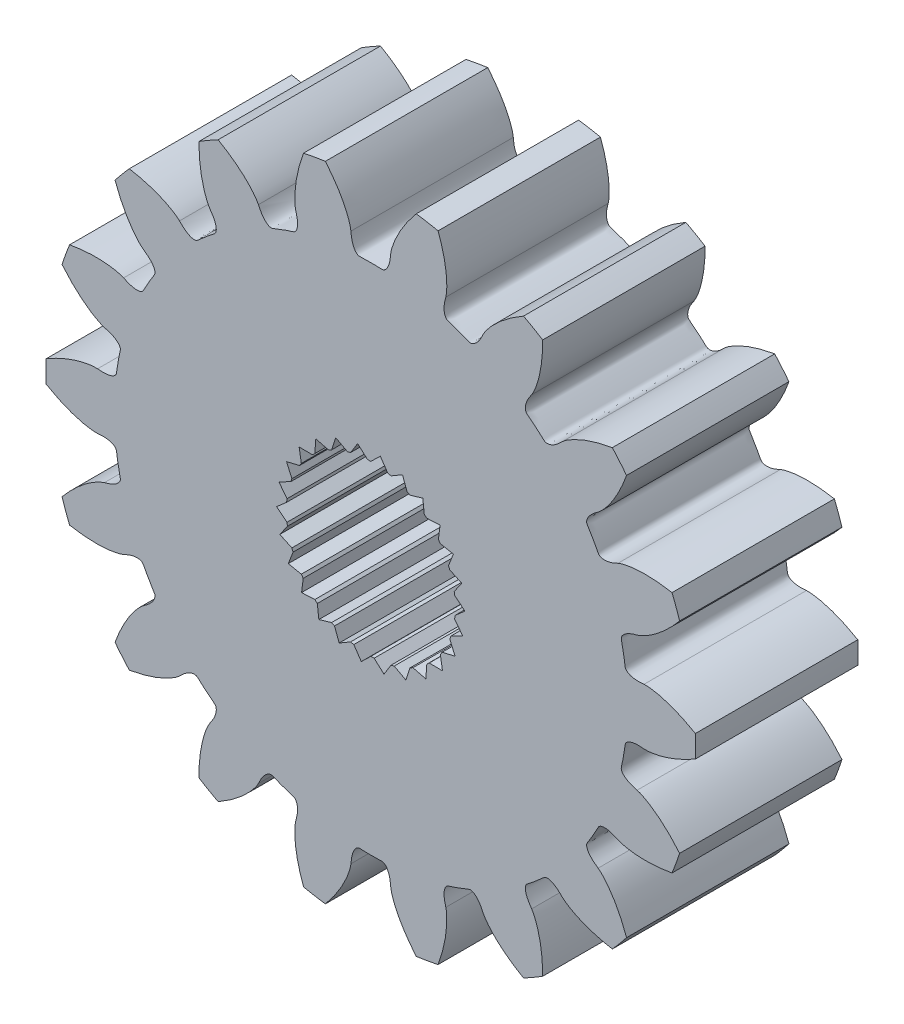
SolidWorks part; units mm, degrees
ref_plane "Ön Düzlem" through (0, 0, 0) normal (0, 0, 1) x (1, 0, 0)
ref_plane "Üst Düzlem" through (0, 0, 0) normal (0, 1, 0) x (1, 0, 0)
ref_plane "Sağ Düzlem" through (0, 0, 0) normal (1, 0, 0) x (0, 0, -1)
sketch "Model" plane through (0, 0, 0) normal (0, 0, 1) x (1, 0, 0)
  arc A0 (-4.7019, 8.8256) -> (-5.2923, 8.4848) centre (0, 0) ccw
  arc A1 (-7.4369, 6.6852) -> (-7.8751, 6.1631) centre (0, 0) ccw
  arc A2 (-9.2749, 3.7385) -> (-9.508, 3.098) centre (0, 0) ccw
  arc A3 (-9.9942, 0.3408) -> (-9.9942, -0.3408) centre (0, 0) ccw
  arc A4 (-9.508, -3.098) -> (-9.2749, -3.7385) centre (0, 0) ccw
  arc A5 (-7.8751, -6.1631) -> (-7.4369, -6.6852) centre (0, 0) ccw
  arc A6 (-5.2923, -8.4848) -> (-4.7019, -8.8256) centre (0, 0) ccw
  arc A7 (-2.0711, -9.7832) -> (-1.3998, -9.9015) centre (0, 0) ccw
  arc A8 (1.3998, -9.9015) -> (2.0711, -9.7832) centre (0, 0) ccw
  arc A9 (4.7019, -8.8256) -> (5.2923, -8.4848) centre (0, 0) ccw
  arc A10 (7.4369, -6.6852) -> (7.8751, -6.1631) centre (0, 0) ccw
  arc A11 (9.2749, -3.7385) -> (9.508, -3.098) centre (0, 0) ccw
  arc A12 (9.9942, -0.3408) -> (9.9942, 0.3408) centre (0, 0) ccw
  arc A13 (9.508, 3.098) -> (9.2749, 3.7385) centre (0, 0) ccw
  arc A14 (7.8751, 6.1631) -> (7.4369, 6.6852) centre (0, 0) ccw
  arc A15 (5.2923, 8.4848) -> (4.7019, 8.8256) centre (0, 0) ccw
  arc A16 (2.0711, 9.7832) -> (1.3998, 9.9015) centre (0, 0) ccw
  arc A17 (-1.3998, 9.9015) -> (-2.0711, 9.7832) centre (0, 0) ccw
  spline S0 degree 3 poles (-3.4596, 7.7174) (-3.4766, 7.7481) (-3.5107, 7.8095) (-3.5724, 7.8948) (-3.6377, 7.9773) (-3.73, 8.083) (-3.8528, 8.2083) (-4.0096, 8.3488) (-4.1738, 8.4805) (-4.3445, 8.6036) (-4.5202, 8.7195) (-4.6414, 8.7902) (-4.7019, 8.8256) knots -0.168309 -0.168309 -0.168309 -0.168309 -0.157796 -0.147277 -0.136757 -0.126236 -0.105199 -0.08416 -0.06312 -0.04208 -0.02104 0 0 0 0
  spline S1 degree 3 poles (-5.2923, 8.4848) (-5.2919, 8.4147) (-5.2912, 8.2744) (-5.2787, 8.0643) (-5.2574, 7.8549) (-5.2255, 7.6468) (-5.1822, 7.4408) (-5.1351, 7.2718) (-5.0897, 7.139) (-5.0509, 7.0412) (-5.0079, 6.9451) (-4.9717, 6.8849) (-4.9537, 6.8548) knots -0.168309 -0.168309 -0.168309 -0.168309 -0.147269 -0.126229 -0.105189 -0.084149 -0.06311 -0.042073 -0.031553 -0.021033 -0.010514 0 0 0 0
  spline S2 degree 3 poles (-4.9537, 6.8548) (-4.9296, 6.8211) (-4.8815, 6.7537) (-4.8313, 6.6629) (-4.7979, 6.5872) (-4.7774, 6.5285) (-4.7628, 6.468) (-4.7564, 6.4061) (-4.761, 6.354) (-4.7741, 6.3146) (-4.7945, 6.2781) (-4.8353, 6.2449) (-4.9017, 6.196) (-4.9834, 6.1322) (-5.0778, 6.0514) (-5.1737, 5.9726) (-5.2507, 5.9031) (-5.3103, 5.8463) (-5.3502, 5.8119) (-5.3897, 5.798) (-5.4307, 5.792) (-5.4828, 5.7965) (-5.5427, 5.8136) (-5.5997, 5.8385) (-5.6539, 5.8688) (-5.7228, 5.9149) (-5.8035, 5.9801) (-5.8615, 6.0392) (-5.8905, 6.0688) knots -0.198614 -0.198614 -0.198614 -0.198614 -0.186198 -0.173785 -0.167576 -0.161368 -0.155161 -0.148957 -0.14276 -0.139657 -0.136554 -0.130358 -0.124146 -0.111726 -0.099307 -0.086888 -0.074468 -0.068256 -0.06206 -0.058957 -0.055854 -0.049658 -0.043453 -0.037246 -0.031038 -0.024829 -0.012416 0 0 0 0
  spline S3 degree 3 poles (-5.8905, 6.0688) (-5.917, 6.0918) (-5.9699, 6.1378) (-6.0572, 6.1969) (-6.1467, 6.2521) (-6.2696, 6.3198) (-6.4279, 6.3955) (-6.6232, 6.474) (-6.8226, 6.5415) (-7.0251, 6.5989) (-7.2299, 6.6476) (-7.3679, 6.6727) (-7.4369, 6.6852) knots -0.168309 -0.168309 -0.168309 -0.168309 -0.157796 -0.147277 -0.136757 -0.126236 -0.105199 -0.08416 -0.06312 -0.04208 -0.02104 0 0 0 0
  spline S4 degree 3 poles (-7.8751, 6.1631) (-7.8507, 6.0973) (-7.8021, 5.9657) (-7.7185, 5.7725) (-7.6269, 5.583) (-7.5257, 5.3984) (-7.4146, 5.2197) (-7.3125, 5.0769) (-7.2244, 4.9677) (-7.1545, 4.8891) (-7.0812, 4.8134) (-7.0267, 4.7693) (-6.9994, 4.7472) knots -0.168309 -0.168309 -0.168309 -0.168309 -0.147269 -0.126229 -0.105189 -0.084149 -0.06311 -0.042073 -0.031553 -0.021033 -0.010514 0 0 0 0
  spline S5 degree 3 poles (-6.9994, 4.7472) (-6.9653, 4.7237) (-6.897, 4.6769) (-6.8188, 4.6087) (-6.7615, 4.5489) (-6.7222, 4.5008) (-6.6878, 4.4489) (-6.6605, 4.393) (-6.6471, 4.3424) (-6.6459, 4.301) (-6.6526, 4.2597) (-6.6796, 4.2145) (-6.7252, 4.1459) (-6.7802, 4.0579) (-6.8413, 3.9498) (-6.9044, 3.8429) (-6.953, 3.7513) (-6.9896, 3.6775) (-7.0153, 3.6315) (-7.0477, 3.605) (-7.0842, 3.5853) (-7.1347, 3.5717) (-7.1968, 3.5673) (-7.2589, 3.5712) (-7.3202, 3.5811) (-7.4007, 3.6009) (-7.4988, 3.6346) (-7.5735, 3.6703) (-7.6109, 3.6881) knots -0.198614 -0.198614 -0.198614 -0.198614 -0.186198 -0.173785 -0.167576 -0.161368 -0.155161 -0.148957 -0.14276 -0.139657 -0.136554 -0.130358 -0.124146 -0.111726 -0.099307 -0.086888 -0.074468 -0.068256 -0.06206 -0.058957 -0.055854 -0.049658 -0.043453 -0.037246 -0.031038 -0.024829 -0.012416 0 0 0 0
  spline S6 degree 3 poles (-7.6109, 3.6881) (-7.6436, 3.7007) (-7.7092, 3.7258) (-7.8113, 3.7515) (-7.9144, 3.7727) (-8.053, 3.7944) (-8.2276, 3.8114) (-8.438, 3.8183) (-8.6485, 3.8135) (-8.8584, 3.7982) (-9.0675, 3.774) (-9.2058, 3.7503) (-9.2749, 3.7385) knots -0.168309 -0.168309 -0.168309 -0.168309 -0.157796 -0.147277 -0.136757 -0.126236 -0.105199 -0.08416 -0.06312 -0.04208 -0.02104 0 0 0 0
  spline S7 degree 3 poles (-9.508, 3.098) (-9.4627, 3.0444) (-9.3719, 2.9374) (-9.2273, 2.7845) (-9.0764, 2.6378) (-8.9182, 2.4989) (-8.7526, 2.369) (-8.6079, 2.2697) (-8.4878, 2.1972) (-8.3952, 2.1472) (-8.3004, 2.1012) (-8.2341, 2.0784) (-8.2009, 2.0669) knots -0.168309 -0.168309 -0.168309 -0.168309 -0.147269 -0.126229 -0.105189 -0.084149 -0.06311 -0.042073 -0.031553 -0.021033 -0.010514 0 0 0 0
  spline S8 degree 3 poles (-8.2009, 2.0669) (-8.1609, 2.0566) (-8.0807, 2.0359) (-7.9838, 1.9986) (-7.9095, 1.962) (-7.8561, 1.9302) (-7.8061, 1.8933) (-7.7614, 1.85) (-7.7314, 1.8071) (-7.7161, 1.7686) (-7.7083, 1.7275) (-7.7182, 1.6758) (-7.7376, 1.5957) (-7.7592, 1.4942) (-7.7796, 1.3718) (-7.8023, 1.2497) (-7.8167, 1.147) (-7.8259, 1.0651) (-7.8343, 1.0131) (-7.8556, 0.9771) (-7.8832, 0.9462) (-7.926, 0.9161) (-7.9829, 0.8907) (-8.0425, 0.8731) (-8.1036, 0.8615) (-8.1859, 0.8525) (-8.2897, 0.8507) (-8.3721, 0.8586) (-8.4133, 0.8626) knots -0.198614 -0.198614 -0.198614 -0.198614 -0.186198 -0.173785 -0.167576 -0.161368 -0.155161 -0.148957 -0.14276 -0.139657 -0.136554 -0.130358 -0.124146 -0.111726 -0.099307 -0.086888 -0.074468 -0.068256 -0.06206 -0.058957 -0.055854 -0.049658 -0.043453 -0.037246 -0.031038 -0.024829 -0.012416 0 0 0 0
  spline S9 degree 3 poles (-8.4133, 0.8626) (-8.4484, 0.8632) (-8.5185, 0.8644) (-8.6233, 0.8536) (-8.7274, 0.8383) (-8.8651, 0.8112) (-9.035, 0.7675) (-9.2351, 0.702) (-9.4312, 0.6256) (-9.6232, 0.5394) (-9.8114, 0.4451) (-9.9333, 0.3756) (-9.9942, 0.3408) knots -0.168309 -0.168309 -0.168309 -0.168309 -0.157796 -0.147277 -0.136757 -0.126236 -0.105199 -0.08416 -0.06312 -0.04208 -0.02104 0 0 0 0
  spline S10 degree 3 poles (-9.9942, -0.3408) (-9.9333, -0.3756) (-9.8114, -0.4451) (-9.6232, -0.5394) (-9.4312, -0.6256) (-9.2351, -0.702) (-9.035, -0.7675) (-8.8651, -0.8112) (-8.7274, -0.8383) (-8.6233, -0.8536) (-8.5185, -0.8644) (-8.4484, -0.8632) (-8.4133, -0.8626) knots -0.168309 -0.168309 -0.168309 -0.168309 -0.147269 -0.126229 -0.105189 -0.084149 -0.06311 -0.042073 -0.031553 -0.021033 -0.010514 0 0 0 0
  spline S11 degree 3 poles (-8.4133, -0.8626) (-8.3721, -0.8586) (-8.2897, -0.8507) (-8.1859, -0.8525) (-8.1036, -0.8615) (-8.0425, -0.8731) (-7.9829, -0.8907) (-7.926, -0.9161) (-7.8832, -0.9462) (-7.8556, -0.9771) (-7.8343, -1.0131) (-7.8259, -1.0651) (-7.8167, -1.147) (-7.8023, -1.2497) (-7.7796, -1.3718) (-7.7592, -1.4942) (-7.7376, -1.5957) (-7.7182, -1.6758) (-7.7083, -1.7275) (-7.7161, -1.7686) (-7.7314, -1.8071) (-7.7614, -1.85) (-7.8061, -1.8933) (-7.8561, -1.9302) (-7.9095, -1.962) (-7.9838, -1.9986) (-8.0807, -2.0359) (-8.1609, -2.0566) (-8.2009, -2.0669) knots -0.198614 -0.198614 -0.198614 -0.198614 -0.186198 -0.173785 -0.167576 -0.161368 -0.155161 -0.148957 -0.14276 -0.139657 -0.136554 -0.130358 -0.124146 -0.111726 -0.099307 -0.086888 -0.074468 -0.068256 -0.06206 -0.058957 -0.055854 -0.049658 -0.043453 -0.037246 -0.031038 -0.024829 -0.012416 0 0 0 0
  spline S12 degree 3 poles (-8.2009, -2.0669) (-8.2341, -2.0784) (-8.3004, -2.1012) (-8.3952, -2.1472) (-8.4878, -2.1972) (-8.6079, -2.2697) (-8.7526, -2.369) (-8.9182, -2.4989) (-9.0764, -2.6378) (-9.2273, -2.7845) (-9.3719, -2.9374) (-9.4627, -3.0444) (-9.508, -3.098) knots -0.168309 -0.168309 -0.168309 -0.168309 -0.157796 -0.147277 -0.136757 -0.126236 -0.105199 -0.08416 -0.06312 -0.04208 -0.02104 0 0 0 0
  spline S13 degree 3 poles (-9.2749, -3.7385) (-9.2058, -3.7503) (-9.0675, -3.774) (-8.8584, -3.7982) (-8.6485, -3.8135) (-8.438, -3.8183) (-8.2276, -3.8114) (-8.053, -3.7944) (-7.9144, -3.7727) (-7.8113, -3.7515) (-7.7092, -3.7258) (-7.6436, -3.7007) (-7.6109, -3.6881) knots -0.168309 -0.168309 -0.168309 -0.168309 -0.147269 -0.126229 -0.105189 -0.084149 -0.06311 -0.042073 -0.031553 -0.021033 -0.010514 0 0 0 0
  spline S14 degree 3 poles (-7.6109, -3.6881) (-7.5735, -3.6703) (-7.4988, -3.6346) (-7.4007, -3.6009) (-7.3202, -3.5811) (-7.2589, -3.5712) (-7.1968, -3.5673) (-7.1347, -3.5717) (-7.0842, -3.5853) (-7.0477, -3.605) (-7.0153, -3.6315) (-6.9896, -3.6775) (-6.953, -3.7513) (-6.9044, -3.8429) (-6.8413, -3.9498) (-6.7802, -4.0579) (-6.7252, -4.1459) (-6.6796, -4.2145) (-6.6526, -4.2597) (-6.6459, -4.301) (-6.6471, -4.3424) (-6.6605, -4.393) (-6.6878, -4.4489) (-6.7222, -4.5008) (-6.7615, -4.5489) (-6.8188, -4.6087) (-6.897, -4.6769) (-6.9653, -4.7237) (-6.9994, -4.7472) knots -0.198614 -0.198614 -0.198614 -0.198614 -0.186198 -0.173785 -0.167576 -0.161368 -0.155161 -0.148957 -0.14276 -0.139657 -0.136554 -0.130358 -0.124146 -0.111726 -0.099307 -0.086888 -0.074468 -0.068256 -0.06206 -0.058957 -0.055854 -0.049658 -0.043453 -0.037246 -0.031038 -0.024829 -0.012416 0 0 0 0
  spline S15 degree 3 poles (-6.9994, -4.7472) (-7.0267, -4.7693) (-7.0812, -4.8134) (-7.1545, -4.8891) (-7.2244, -4.9677) (-7.3125, -5.0769) (-7.4146, -5.2197) (-7.5257, -5.3984) (-7.6269, -5.583) (-7.7185, -5.7725) (-7.8021, -5.9657) (-7.8507, -6.0973) (-7.8751, -6.1631) knots -0.168309 -0.168309 -0.168309 -0.168309 -0.157796 -0.147277 -0.136757 -0.126236 -0.105199 -0.08416 -0.06312 -0.04208 -0.02104 0 0 0 0
  spline S16 degree 3 poles (-7.4369, -6.6852) (-7.3679, -6.6727) (-7.2299, -6.6476) (-7.0251, -6.5989) (-6.8226, -6.5415) (-6.6232, -6.474) (-6.4279, -6.3955) (-6.2696, -6.3198) (-6.1467, -6.2521) (-6.0572, -6.1969) (-5.9699, -6.1378) (-5.917, -6.0918) (-5.8905, -6.0688) knots -0.168309 -0.168309 -0.168309 -0.168309 -0.147269 -0.126229 -0.105189 -0.084149 -0.06311 -0.042073 -0.031553 -0.021033 -0.010514 0 0 0 0
  spline S17 degree 3 poles (-5.8905, -6.0688) (-5.8615, -6.0392) (-5.8035, -5.9801) (-5.7228, -5.9149) (-5.6539, -5.8688) (-5.5997, -5.8385) (-5.5427, -5.8136) (-5.4828, -5.7965) (-5.4307, -5.792) (-5.3897, -5.798) (-5.3502, -5.8119) (-5.3103, -5.8463) (-5.2507, -5.9031) (-5.1737, -5.9726) (-5.0778, -6.0514) (-4.9834, -6.1322) (-4.9017, -6.196) (-4.8353, -6.2449) (-4.7945, -6.2781) (-4.7741, -6.3146) (-4.761, -6.354) (-4.7564, -6.4061) (-4.7628, -6.468) (-4.7774, -6.5285) (-4.7979, -6.5872) (-4.8313, -6.6629) (-4.8815, -6.7537) (-4.9296, -6.8211) (-4.9537, -6.8548) knots -0.198614 -0.198614 -0.198614 -0.198614 -0.186198 -0.173785 -0.167576 -0.161368 -0.155161 -0.148957 -0.14276 -0.139657 -0.136554 -0.130358 -0.124146 -0.111726 -0.099307 -0.086888 -0.074468 -0.068256 -0.06206 -0.058957 -0.055854 -0.049658 -0.043453 -0.037246 -0.031038 -0.024829 -0.012416 0 0 0 0
  spline S18 degree 3 poles (-4.9537, -6.8548) (-4.9717, -6.8849) (-5.0079, -6.9451) (-5.0509, -7.0412) (-5.0897, -7.139) (-5.1351, -7.2718) (-5.1822, -7.4408) (-5.2255, -7.6468) (-5.2574, -7.8549) (-5.2787, -8.0643) (-5.2912, -8.2744) (-5.2919, -8.4147) (-5.2923, -8.4848) knots -0.168309 -0.168309 -0.168309 -0.168309 -0.157796 -0.147277 -0.136757 -0.126236 -0.105199 -0.08416 -0.06312 -0.04208 -0.02104 0 0 0 0
  spline S19 degree 3 poles (-4.7019, -8.8256) (-4.6414, -8.7902) (-4.5202, -8.7195) (-4.3445, -8.6036) (-4.1738, -8.4805) (-4.0096, -8.3488) (-3.8528, -8.2083) (-3.73, -8.083) (-3.6377, -7.9773) (-3.5724, -7.8948) (-3.5107, -7.8095) (-3.4766, -7.7481) (-3.4596, -7.7174) knots -0.168309 -0.168309 -0.168309 -0.168309 -0.147269 -0.126229 -0.105189 -0.084149 -0.06311 -0.042073 -0.031553 -0.021033 -0.010514 0 0 0 0
  spline S20 degree 3 poles (-3.4596, -7.7174) (-3.4425, -7.6797) (-3.4081, -7.6044) (-3.3546, -7.5155) (-3.3057, -7.4487) (-3.2651, -7.4016) (-3.22, -7.3587) (-3.1697, -7.3222) (-3.1222, -7.3002) (-3.0816, -7.2918) (-3.0398, -7.2913) (-2.9905, -7.3099) (-2.9151, -7.343) (-2.8189, -7.3819) (-2.7018, -7.4232) (-2.5856, -7.4668) (-2.4869, -7.4988) (-2.4078, -7.522) (-2.3581, -7.5394) (-2.3264, -7.5666) (-2.3007, -7.5992) (-2.2785, -7.6465) (-2.2634, -7.7069) (-2.2564, -7.7687) (-2.2556, -7.8309) (-2.2611, -7.9135) (-2.2772, -8.016) (-2.2994, -8.0958) (-2.3104, -8.1357) knots -0.198614 -0.198614 -0.198614 -0.198614 -0.186198 -0.173785 -0.167576 -0.161368 -0.155161 -0.148957 -0.14276 -0.139657 -0.136554 -0.130358 -0.124146 -0.111726 -0.099307 -0.086888 -0.074468 -0.068256 -0.06206 -0.058957 -0.055854 -0.049658 -0.043453 -0.037246 -0.031038 -0.024829 -0.012416 0 0 0 0
  spline S21 degree 3 poles (-2.3104, -8.1357) (-2.3171, -8.1701) (-2.3305, -8.239) (-2.3381, -8.3441) (-2.3411, -8.4492) (-2.3383, -8.5895) (-2.3247, -8.7645) (-2.295, -8.9729) (-2.2538, -9.1793) (-2.2022, -9.3833) (-2.1421, -9.5851) (-2.0948, -9.7171) (-2.0711, -9.7832) knots -0.168309 -0.168309 -0.168309 -0.168309 -0.157796 -0.147277 -0.136757 -0.126236 -0.105199 -0.08416 -0.06312 -0.04208 -0.02104 0 0 0 0
  spline S22 degree 3 poles (-1.3998, -9.9015) (-1.355, -9.8476) (-1.2654, -9.7396) (-1.1399, -9.5707) (-1.0216, -9.3966) (-0.9123, -9.2167) (-0.8131, -9.031) (-0.7405, -8.8713) (-0.6899, -8.7404) (-0.6568, -8.6405) (-0.6279, -8.5392) (-0.617, -8.4699) (-0.6115, -8.4353) knots -0.168309 -0.168309 -0.168309 -0.168309 -0.147269 -0.126229 -0.105189 -0.084149 -0.06311 -0.042073 -0.031553 -0.021033 -0.010514 0 0 0 0
  spline S23 degree 3 poles (-0.6115, -8.4353) (-0.6082, -8.394) (-0.6018, -8.3114) (-0.5819, -8.2096) (-0.5588, -8.1301) (-0.5367, -8.072) (-0.509, -8.0163) (-0.4742, -7.9647) (-0.4371, -7.9278) (-0.4018, -7.906) (-0.3627, -7.8912) (-0.31, -7.8919) (-0.2278, -7.8972) (-0.1242, -7.9008) (0, -7.8996) (0.1242, -7.9008) (0.2278, -7.8972) (0.31, -7.8919) (0.3627, -7.8912) (0.4018, -7.906) (0.4371, -7.9278) (0.4742, -7.9647) (0.509, -8.0163) (0.5367, -8.072) (0.5588, -8.1301) (0.5819, -8.2096) (0.6018, -8.3114) (0.6082, -8.394) (0.6115, -8.4353) knots -0.198614 -0.198614 -0.198614 -0.198614 -0.186198 -0.173785 -0.167576 -0.161368 -0.155161 -0.148957 -0.14276 -0.139657 -0.136554 -0.130358 -0.124146 -0.111726 -0.099307 -0.086888 -0.074468 -0.068256 -0.06206 -0.058957 -0.055854 -0.049658 -0.043453 -0.037246 -0.031038 -0.024829 -0.012416 0 0 0 0
  spline S24 degree 3 poles (0.6115, -8.4353) (0.617, -8.4699) (0.6279, -8.5392) (0.6568, -8.6405) (0.6899, -8.7404) (0.7405, -8.8713) (0.8131, -9.031) (0.9123, -9.2167) (1.0216, -9.3966) (1.1399, -9.5707) (1.2654, -9.7396) (1.355, -9.8476) (1.3998, -9.9015) knots -0.168309 -0.168309 -0.168309 -0.168309 -0.157796 -0.147277 -0.136757 -0.126236 -0.105199 -0.08416 -0.06312 -0.04208 -0.02104 0 0 0 0
  spline S25 degree 3 poles (2.0711, -9.7832) (2.0948, -9.7171) (2.1421, -9.5851) (2.2022, -9.3833) (2.2538, -9.1793) (2.295, -8.9729) (2.3247, -8.7645) (2.3383, -8.5895) (2.3411, -8.4492) (2.3381, -8.3441) (2.3305, -8.239) (2.3171, -8.1701) (2.3104, -8.1357) knots -0.168309 -0.168309 -0.168309 -0.168309 -0.147269 -0.126229 -0.105189 -0.084149 -0.06311 -0.042073 -0.031553 -0.021033 -0.010514 0 0 0 0
  spline S26 degree 3 poles (2.3104, -8.1357) (2.2994, -8.0958) (2.2772, -8.016) (2.2611, -7.9135) (2.2556, -7.8309) (2.2564, -7.7687) (2.2634, -7.7069) (2.2785, -7.6465) (2.3007, -7.5992) (2.3264, -7.5666) (2.3581, -7.5394) (2.4078, -7.522) (2.4869, -7.4988) (2.5856, -7.4668) (2.7018, -7.4232) (2.8189, -7.3819) (2.9151, -7.343) (2.9905, -7.3099) (3.0398, -7.2913) (3.0816, -7.2918) (3.1222, -7.3002) (3.1697, -7.3222) (3.22, -7.3587) (3.2651, -7.4016) (3.3057, -7.4487) (3.3546, -7.5155) (3.4081, -7.6044) (3.4425, -7.6797) (3.4596, -7.7174) knots -0.198614 -0.198614 -0.198614 -0.198614 -0.186198 -0.173785 -0.167576 -0.161368 -0.155161 -0.148957 -0.14276 -0.139657 -0.136554 -0.130358 -0.124146 -0.111726 -0.099307 -0.086888 -0.074468 -0.068256 -0.06206 -0.058957 -0.055854 -0.049658 -0.043453 -0.037246 -0.031038 -0.024829 -0.012416 0 0 0 0
  spline S27 degree 3 poles (3.4596, -7.7174) (3.4766, -7.7481) (3.5107, -7.8095) (3.5724, -7.8948) (3.6377, -7.9773) (3.73, -8.083) (3.8528, -8.2083) (4.0096, -8.3488) (4.1738, -8.4805) (4.3445, -8.6036) (4.5202, -8.7195) (4.6414, -8.7902) (4.7019, -8.8256) knots -0.168309 -0.168309 -0.168309 -0.168309 -0.157796 -0.147277 -0.136757 -0.126236 -0.105199 -0.08416 -0.06312 -0.04208 -0.02104 0 0 0 0
  spline S28 degree 3 poles (5.2923, -8.4848) (5.2919, -8.4147) (5.2912, -8.2744) (5.2787, -8.0643) (5.2574, -7.8549) (5.2255, -7.6468) (5.1822, -7.4408) (5.1351, -7.2718) (5.0897, -7.139) (5.0509, -7.0412) (5.0079, -6.9451) (4.9717, -6.8849) (4.9537, -6.8548) knots -0.168309 -0.168309 -0.168309 -0.168309 -0.147269 -0.126229 -0.105189 -0.084149 -0.06311 -0.042073 -0.031553 -0.021033 -0.010514 0 0 0 0
  spline S29 degree 3 poles (4.9537, -6.8548) (4.9296, -6.8211) (4.8815, -6.7537) (4.8313, -6.6629) (4.7979, -6.5872) (4.7774, -6.5285) (4.7628, -6.468) (4.7564, -6.4061) (4.761, -6.354) (4.7741, -6.3146) (4.7945, -6.2781) (4.8353, -6.2449) (4.9017, -6.196) (4.9834, -6.1322) (5.0778, -6.0514) (5.1737, -5.9726) (5.2507, -5.9031) (5.3103, -5.8463) (5.3502, -5.8119) (5.3897, -5.798) (5.4307, -5.792) (5.4828, -5.7965) (5.5427, -5.8136) (5.5997, -5.8385) (5.6539, -5.8688) (5.7228, -5.9149) (5.8035, -5.9801) (5.8615, -6.0392) (5.8905, -6.0688) knots -0.198614 -0.198614 -0.198614 -0.198614 -0.186198 -0.173785 -0.167576 -0.161368 -0.155161 -0.148957 -0.14276 -0.139657 -0.136554 -0.130358 -0.124146 -0.111726 -0.099307 -0.086888 -0.074468 -0.068256 -0.06206 -0.058957 -0.055854 -0.049658 -0.043453 -0.037246 -0.031038 -0.024829 -0.012416 0 0 0 0
  spline S30 degree 3 poles (5.8905, -6.0688) (5.917, -6.0918) (5.9699, -6.1378) (6.0572, -6.1969) (6.1467, -6.2521) (6.2696, -6.3198) (6.4279, -6.3955) (6.6232, -6.474) (6.8226, -6.5415) (7.0251, -6.5989) (7.2299, -6.6476) (7.3679, -6.6727) (7.4369, -6.6852) knots -0.168309 -0.168309 -0.168309 -0.168309 -0.157796 -0.147277 -0.136757 -0.126236 -0.105199 -0.08416 -0.06312 -0.04208 -0.02104 0 0 0 0
  spline S31 degree 3 poles (7.8751, -6.1631) (7.8507, -6.0973) (7.8021, -5.9657) (7.7185, -5.7725) (7.6269, -5.583) (7.5257, -5.3984) (7.4146, -5.2197) (7.3125, -5.0769) (7.2244, -4.9677) (7.1545, -4.8891) (7.0812, -4.8134) (7.0267, -4.7693) (6.9994, -4.7472) knots -0.168309 -0.168309 -0.168309 -0.168309 -0.147269 -0.126229 -0.105189 -0.084149 -0.06311 -0.042073 -0.031553 -0.021033 -0.010514 0 0 0 0
  spline S32 degree 3 poles (6.9994, -4.7472) (6.9653, -4.7237) (6.897, -4.6769) (6.8188, -4.6087) (6.7615, -4.5489) (6.7222, -4.5008) (6.6878, -4.4489) (6.6605, -4.393) (6.6471, -4.3424) (6.6459, -4.301) (6.6526, -4.2597) (6.6796, -4.2145) (6.7252, -4.1459) (6.7802, -4.0579) (6.8413, -3.9498) (6.9044, -3.8429) (6.953, -3.7513) (6.9896, -3.6775) (7.0153, -3.6315) (7.0477, -3.605) (7.0842, -3.5853) (7.1347, -3.5717) (7.1968, -3.5673) (7.2589, -3.5712) (7.3202, -3.5811) (7.4007, -3.6009) (7.4988, -3.6346) (7.5735, -3.6703) (7.6109, -3.6881) knots -0.198614 -0.198614 -0.198614 -0.198614 -0.186198 -0.173785 -0.167576 -0.161368 -0.155161 -0.148957 -0.14276 -0.139657 -0.136554 -0.130358 -0.124146 -0.111726 -0.099307 -0.086888 -0.074468 -0.068256 -0.06206 -0.058957 -0.055854 -0.049658 -0.043453 -0.037246 -0.031038 -0.024829 -0.012416 0 0 0 0
  spline S33 degree 3 poles (7.6109, -3.6881) (7.6436, -3.7007) (7.7092, -3.7258) (7.8113, -3.7515) (7.9144, -3.7727) (8.053, -3.7944) (8.2276, -3.8114) (8.438, -3.8183) (8.6485, -3.8135) (8.8584, -3.7982) (9.0675, -3.774) (9.2058, -3.7503) (9.2749, -3.7385) knots -0.168309 -0.168309 -0.168309 -0.168309 -0.157796 -0.147277 -0.136757 -0.126236 -0.105199 -0.08416 -0.06312 -0.04208 -0.02104 0 0 0 0
  spline S34 degree 3 poles (9.508, -3.098) (9.4627, -3.0444) (9.3719, -2.9374) (9.2273, -2.7845) (9.0764, -2.6378) (8.9182, -2.4989) (8.7526, -2.369) (8.6079, -2.2697) (8.4878, -2.1972) (8.3952, -2.1472) (8.3004, -2.1012) (8.2341, -2.0784) (8.2009, -2.0669) knots -0.168309 -0.168309 -0.168309 -0.168309 -0.147269 -0.126229 -0.105189 -0.084149 -0.06311 -0.042073 -0.031553 -0.021033 -0.010514 0 0 0 0
  spline S35 degree 3 poles (8.2009, -2.0669) (8.1609, -2.0566) (8.0807, -2.0359) (7.9838, -1.9986) (7.9095, -1.962) (7.8561, -1.9302) (7.8061, -1.8933) (7.7614, -1.85) (7.7314, -1.8071) (7.7161, -1.7686) (7.7083, -1.7275) (7.7182, -1.6758) (7.7376, -1.5957) (7.7592, -1.4942) (7.7796, -1.3718) (7.8023, -1.2497) (7.8167, -1.147) (7.8259, -1.0651) (7.8343, -1.0131) (7.8556, -0.9771) (7.8832, -0.9462) (7.926, -0.9161) (7.9829, -0.8907) (8.0425, -0.8731) (8.1036, -0.8615) (8.1859, -0.8525) (8.2897, -0.8507) (8.3721, -0.8586) (8.4133, -0.8626) knots -0.198614 -0.198614 -0.198614 -0.198614 -0.186198 -0.173785 -0.167576 -0.161368 -0.155161 -0.148957 -0.14276 -0.139657 -0.136554 -0.130358 -0.124146 -0.111726 -0.099307 -0.086888 -0.074468 -0.068256 -0.06206 -0.058957 -0.055854 -0.049658 -0.043453 -0.037246 -0.031038 -0.024829 -0.012416 0 0 0 0
  spline S36 degree 3 poles (8.4133, -0.8626) (8.4484, -0.8632) (8.5185, -0.8644) (8.6233, -0.8536) (8.7274, -0.8383) (8.8651, -0.8112) (9.035, -0.7675) (9.2351, -0.702) (9.4312, -0.6256) (9.6232, -0.5394) (9.8114, -0.4451) (9.9333, -0.3756) (9.9942, -0.3408) knots -0.168309 -0.168309 -0.168309 -0.168309 -0.157796 -0.147277 -0.136757 -0.126236 -0.105199 -0.08416 -0.06312 -0.04208 -0.02104 0 0 0 0
  spline S37 degree 3 poles (9.9942, 0.3408) (9.9333, 0.3756) (9.8114, 0.4451) (9.6232, 0.5394) (9.4312, 0.6256) (9.2351, 0.702) (9.035, 0.7675) (8.8651, 0.8112) (8.7274, 0.8383) (8.6233, 0.8536) (8.5185, 0.8644) (8.4484, 0.8632) (8.4133, 0.8626) knots -0.168309 -0.168309 -0.168309 -0.168309 -0.147269 -0.126229 -0.105189 -0.084149 -0.06311 -0.042073 -0.031553 -0.021033 -0.010514 0 0 0 0
  spline S38 degree 3 poles (8.4133, 0.8626) (8.3721, 0.8586) (8.2897, 0.8507) (8.1859, 0.8525) (8.1036, 0.8615) (8.0425, 0.8731) (7.9829, 0.8907) (7.926, 0.9161) (7.8832, 0.9462) (7.8556, 0.9771) (7.8343, 1.0131) (7.8259, 1.0651) (7.8167, 1.147) (7.8023, 1.2497) (7.7796, 1.3718) (7.7592, 1.4942) (7.7376, 1.5957) (7.7182, 1.6758) (7.7083, 1.7275) (7.7161, 1.7686) (7.7314, 1.8071) (7.7614, 1.85) (7.8061, 1.8933) (7.8561, 1.9302) (7.9095, 1.962) (7.9838, 1.9986) (8.0807, 2.0359) (8.1609, 2.0566) (8.2009, 2.0669) knots -0.198614 -0.198614 -0.198614 -0.198614 -0.186198 -0.173785 -0.167576 -0.161368 -0.155161 -0.148957 -0.14276 -0.139657 -0.136554 -0.130358 -0.124146 -0.111726 -0.099307 -0.086888 -0.074468 -0.068256 -0.06206 -0.058957 -0.055854 -0.049658 -0.043453 -0.037246 -0.031038 -0.024829 -0.012416 0 0 0 0
  spline S39 degree 3 poles (8.2009, 2.0669) (8.2341, 2.0784) (8.3004, 2.1012) (8.3952, 2.1472) (8.4878, 2.1972) (8.6079, 2.2697) (8.7526, 2.369) (8.9182, 2.4989) (9.0764, 2.6378) (9.2273, 2.7845) (9.3719, 2.9374) (9.4627, 3.0444) (9.508, 3.098) knots -0.168309 -0.168309 -0.168309 -0.168309 -0.157796 -0.147277 -0.136757 -0.126236 -0.105199 -0.08416 -0.06312 -0.04208 -0.02104 0 0 0 0
  spline S40 degree 3 poles (9.2749, 3.7385) (9.2058, 3.7503) (9.0675, 3.774) (8.8584, 3.7982) (8.6485, 3.8135) (8.438, 3.8183) (8.2276, 3.8114) (8.053, 3.7944) (7.9144, 3.7727) (7.8113, 3.7515) (7.7092, 3.7258) (7.6436, 3.7007) (7.6109, 3.6881) knots -0.168309 -0.168309 -0.168309 -0.168309 -0.147269 -0.126229 -0.105189 -0.084149 -0.06311 -0.042073 -0.031553 -0.021033 -0.010514 0 0 0 0
  spline S41 degree 3 poles (7.6109, 3.6881) (7.5735, 3.6703) (7.4988, 3.6346) (7.4007, 3.6009) (7.3202, 3.5811) (7.2589, 3.5712) (7.1968, 3.5673) (7.1347, 3.5717) (7.0842, 3.5853) (7.0477, 3.605) (7.0153, 3.6315) (6.9896, 3.6775) (6.953, 3.7513) (6.9044, 3.8429) (6.8413, 3.9498) (6.7802, 4.0579) (6.7252, 4.1459) (6.6796, 4.2145) (6.6526, 4.2597) (6.6459, 4.301) (6.6471, 4.3424) (6.6605, 4.393) (6.6878, 4.4489) (6.7222, 4.5008) (6.7615, 4.5489) (6.8188, 4.6087) (6.897, 4.6769) (6.9653, 4.7237) (6.9994, 4.7472) knots -0.198614 -0.198614 -0.198614 -0.198614 -0.186198 -0.173785 -0.167576 -0.161368 -0.155161 -0.148957 -0.14276 -0.139657 -0.136554 -0.130358 -0.124146 -0.111726 -0.099307 -0.086888 -0.074468 -0.068256 -0.06206 -0.058957 -0.055854 -0.049658 -0.043453 -0.037246 -0.031038 -0.024829 -0.012416 0 0 0 0
  spline S42 degree 3 poles (6.9994, 4.7472) (7.0267, 4.7693) (7.0812, 4.8134) (7.1545, 4.8891) (7.2244, 4.9677) (7.3125, 5.0769) (7.4146, 5.2197) (7.5257, 5.3984) (7.6269, 5.583) (7.7185, 5.7725) (7.8021, 5.9657) (7.8507, 6.0973) (7.8751, 6.1631) knots -0.168309 -0.168309 -0.168309 -0.168309 -0.157796 -0.147277 -0.136757 -0.126236 -0.105199 -0.08416 -0.06312 -0.04208 -0.02104 0 0 0 0
  spline S43 degree 3 poles (7.4369, 6.6852) (7.3679, 6.6727) (7.2299, 6.6476) (7.0251, 6.5989) (6.8226, 6.5415) (6.6232, 6.474) (6.4279, 6.3955) (6.2696, 6.3198) (6.1467, 6.2521) (6.0572, 6.1969) (5.9699, 6.1378) (5.917, 6.0918) (5.8905, 6.0688) knots -0.168309 -0.168309 -0.168309 -0.168309 -0.147269 -0.126229 -0.105189 -0.084149 -0.06311 -0.042073 -0.031553 -0.021033 -0.010514 0 0 0 0
  spline S44 degree 3 poles (5.8905, 6.0688) (5.8615, 6.0392) (5.8035, 5.9801) (5.7228, 5.9149) (5.6539, 5.8688) (5.5997, 5.8385) (5.5427, 5.8136) (5.4828, 5.7965) (5.4307, 5.792) (5.3897, 5.798) (5.3502, 5.8119) (5.3103, 5.8463) (5.2507, 5.9031) (5.1737, 5.9726) (5.0778, 6.0514) (4.9834, 6.1322) (4.9017, 6.196) (4.8353, 6.2449) (4.7945, 6.2781) (4.7741, 6.3146) (4.761, 6.354) (4.7564, 6.4061) (4.7628, 6.468) (4.7774, 6.5285) (4.7979, 6.5872) (4.8313, 6.6629) (4.8815, 6.7537) (4.9296, 6.8211) (4.9537, 6.8548) knots -0.198614 -0.198614 -0.198614 -0.198614 -0.186198 -0.173785 -0.167576 -0.161368 -0.155161 -0.148957 -0.14276 -0.139657 -0.136554 -0.130358 -0.124146 -0.111726 -0.099307 -0.086888 -0.074468 -0.068256 -0.06206 -0.058957 -0.055854 -0.049658 -0.043453 -0.037246 -0.031038 -0.024829 -0.012416 0 0 0 0
  spline S45 degree 3 poles (4.9537, 6.8548) (4.9717, 6.8849) (5.0079, 6.9451) (5.0509, 7.0412) (5.0897, 7.139) (5.1351, 7.2718) (5.1822, 7.4408) (5.2255, 7.6468) (5.2574, 7.8549) (5.2787, 8.0643) (5.2912, 8.2744) (5.2919, 8.4147) (5.2923, 8.4848) knots -0.168309 -0.168309 -0.168309 -0.168309 -0.157796 -0.147277 -0.136757 -0.126236 -0.105199 -0.08416 -0.06312 -0.04208 -0.02104 0 0 0 0
  spline S46 degree 3 poles (4.7019, 8.8256) (4.6414, 8.7902) (4.5202, 8.7195) (4.3445, 8.6036) (4.1738, 8.4805) (4.0096, 8.3488) (3.8528, 8.2083) (3.73, 8.083) (3.6377, 7.9773) (3.5724, 7.8948) (3.5107, 7.8095) (3.4766, 7.7481) (3.4596, 7.7174) knots -0.168309 -0.168309 -0.168309 -0.168309 -0.147269 -0.126229 -0.105189 -0.084149 -0.06311 -0.042073 -0.031553 -0.021033 -0.010514 0 0 0 0
  spline S47 degree 3 poles (3.4596, 7.7174) (3.4425, 7.6797) (3.4081, 7.6044) (3.3546, 7.5155) (3.3057, 7.4487) (3.2651, 7.4016) (3.22, 7.3587) (3.1697, 7.3222) (3.1222, 7.3002) (3.0816, 7.2918) (3.0398, 7.2913) (2.9905, 7.3099) (2.9151, 7.343) (2.8189, 7.3819) (2.7018, 7.4232) (2.5856, 7.4668) (2.4869, 7.4988) (2.4078, 7.522) (2.3581, 7.5394) (2.3264, 7.5666) (2.3007, 7.5992) (2.2785, 7.6465) (2.2634, 7.7069) (2.2564, 7.7687) (2.2556, 7.8309) (2.2611, 7.9135) (2.2772, 8.016) (2.2994, 8.0958) (2.3104, 8.1357) knots -0.198614 -0.198614 -0.198614 -0.198614 -0.186198 -0.173785 -0.167576 -0.161368 -0.155161 -0.148957 -0.14276 -0.139657 -0.136554 -0.130358 -0.124146 -0.111726 -0.099307 -0.086888 -0.074468 -0.068256 -0.06206 -0.058957 -0.055854 -0.049658 -0.043453 -0.037246 -0.031038 -0.024829 -0.012416 0 0 0 0
  spline S48 degree 3 poles (2.3104, 8.1357) (2.3171, 8.1701) (2.3305, 8.239) (2.3381, 8.3441) (2.3411, 8.4492) (2.3383, 8.5895) (2.3247, 8.7645) (2.295, 8.9729) (2.2538, 9.1793) (2.2022, 9.3833) (2.1421, 9.5851) (2.0948, 9.7171) (2.0711, 9.7832) knots -0.168309 -0.168309 -0.168309 -0.168309 -0.157796 -0.147277 -0.136757 -0.126236 -0.105199 -0.08416 -0.06312 -0.04208 -0.02104 0 0 0 0
  spline S49 degree 3 poles (1.3998, 9.9015) (1.355, 9.8476) (1.2654, 9.7396) (1.1399, 9.5707) (1.0216, 9.3966) (0.9123, 9.2167) (0.8131, 9.031) (0.7405, 8.8713) (0.6899, 8.7404) (0.6568, 8.6405) (0.6279, 8.5392) (0.617, 8.4699) (0.6115, 8.4353) knots -0.168309 -0.168309 -0.168309 -0.168309 -0.147269 -0.126229 -0.105189 -0.084149 -0.06311 -0.042073 -0.031553 -0.021033 -0.010514 0 0 0 0
  spline S50 degree 3 poles (0.6115, 8.4353) (0.6082, 8.394) (0.6018, 8.3114) (0.5819, 8.2096) (0.5588, 8.1301) (0.5367, 8.072) (0.509, 8.0163) (0.4742, 7.9647) (0.4371, 7.9278) (0.4018, 7.906) (0.3627, 7.8912) (0.31, 7.8919) (0.2278, 7.8972) (0.1242, 7.9008) (0, 7.8996) (-0.1242, 7.9008) (-0.2278, 7.8972) (-0.31, 7.8919) (-0.3627, 7.8912) (-0.4018, 7.906) (-0.4371, 7.9278) (-0.4742, 7.9647) (-0.509, 8.0163) (-0.5367, 8.072) (-0.5588, 8.1301) (-0.5819, 8.2096) (-0.6018, 8.3114) (-0.6082, 8.394) (-0.6115, 8.4353) knots -0.198614 -0.198614 -0.198614 -0.198614 -0.186198 -0.173785 -0.167576 -0.161368 -0.155161 -0.148957 -0.14276 -0.139657 -0.136554 -0.130358 -0.124146 -0.111726 -0.099307 -0.086888 -0.074468 -0.068256 -0.06206 -0.058957 -0.055854 -0.049658 -0.043453 -0.037246 -0.031038 -0.024829 -0.012416 0 0 0 0
  spline S51 degree 3 poles (-0.6115, 8.4353) (-0.617, 8.4699) (-0.6279, 8.5392) (-0.6568, 8.6405) (-0.6899, 8.7404) (-0.7405, 8.8713) (-0.8131, 9.031) (-0.9123, 9.2167) (-1.0216, 9.3966) (-1.1399, 9.5707) (-1.2654, 9.7396) (-1.355, 9.8476) (-1.3998, 9.9015) knots -0.168309 -0.168309 -0.168309 -0.168309 -0.157796 -0.147277 -0.136757 -0.126236 -0.105199 -0.08416 -0.06312 -0.04208 -0.02104 0 0 0 0
  spline S52 degree 3 poles (-2.0711, 9.7832) (-2.0948, 9.7171) (-2.1421, 9.5851) (-2.2022, 9.3833) (-2.2538, 9.1793) (-2.295, 8.9729) (-2.3247, 8.7645) (-2.3383, 8.5895) (-2.3411, 8.4492) (-2.3381, 8.3441) (-2.3305, 8.239) (-2.3171, 8.1701) (-2.3104, 8.1357) knots -0.168309 -0.168309 -0.168309 -0.168309 -0.147269 -0.126229 -0.105189 -0.084149 -0.06311 -0.042073 -0.031553 -0.021033 -0.010514 0 0 0 0
  spline S53 degree 3 poles (-2.3104, 8.1357) (-2.2994, 8.0958) (-2.2772, 8.016) (-2.2611, 7.9135) (-2.2556, 7.8309) (-2.2564, 7.7687) (-2.2634, 7.7069) (-2.2785, 7.6465) (-2.3007, 7.5992) (-2.3264, 7.5666) (-2.3581, 7.5394) (-2.4078, 7.522) (-2.4869, 7.4988) (-2.5856, 7.4668) (-2.7018, 7.4232) (-2.8189, 7.3819) (-2.9151, 7.343) (-2.9905, 7.3099) (-3.0398, 7.2913) (-3.0816, 7.2918) (-3.1222, 7.3002) (-3.1697, 7.3222) (-3.22, 7.3587) (-3.2651, 7.4016) (-3.3057, 7.4487) (-3.3546, 7.5155) (-3.4081, 7.6044) (-3.4425, 7.6797) (-3.4596, 7.7174) knots -0.198614 -0.198614 -0.198614 -0.198614 -0.186198 -0.173785 -0.167576 -0.161368 -0.155161 -0.148957 -0.14276 -0.139657 -0.136554 -0.130358 -0.124146 -0.111726 -0.099307 -0.086888 -0.074468 -0.068256 -0.06206 -0.058957 -0.055854 -0.049658 -0.043453 -0.037246 -0.031038 -0.024829 -0.012416 0 0 0 0
extrude "Boss-Extrude1" add sketch "Model" along normal blind 5
sketch "Çizim1" plane through (0, 0, 5) normal (0, 0, 1) x (1, 0, 0)
  line L0 (0, 2.6) -> (0.2932, 2.8851)
  line L1 (0.2932, 2.8851) -> (0.5231, 2.5468)
  line L2 (0.2932, 2.8851) -> (0.2629, 2.5867) construction
  line L3 (0.6222, 2.5244) -> (0.9752, 2.7311)
  line L4 (0.9752, 2.7311) -> (1.1174, 2.3476)
  line L5 (0.9752, 2.7311) -> (0.8743, 2.4486) construction
  line L6 (1.2083, 2.3022) -> (1.6004, 2.4184)
  line L7 (1.6004, 2.4184) -> (1.6468, 2.012)
  line L8 (1.6004, 2.4184) -> (1.4349, 2.1682) construction
  line L9 (1.7241, 1.9461) -> (2.1327, 1.9651)
  line L10 (2.1327, 1.9651) -> (2.0804, 1.5594)
  line L11 (2.1327, 1.9651) -> (1.9121, 1.7618) construction
  line L12 (2.1398, 1.477) -> (2.541, 1.3976)
  line L13 (2.541, 1.3976) -> (2.3932, 1.0162)
  line L14 (2.541, 1.3976) -> (2.2781, 1.253) construction
  line L15 (2.431, 0.922) -> (2.8016, 0.7489)
  line L16 (2.8016, 0.7489) -> (2.5668, 0.414)
  line L17 (2.8016, 0.7489) -> (2.5118, 0.6714) construction
  line L18 (2.581, 0.3134) -> (2.8994, 0.0567)
  line L19 (2.8994, 0.0567) -> (2.5913, -0.2123)
  line L20 (2.8994, 0.0567) -> (2.5995, 0.0508) construction
  line L21 (2.581, -0.3134) -> (2.8288, -0.6389)
  line L22 (2.8288, -0.6389) -> (2.4652, -0.8263)
  line L23 (2.8288, -0.6389) -> (2.5361, -0.5728) construction
  line L24 (2.431, -0.922) -> (2.5937, -1.2973)
  line L25 (2.5937, -1.2973) -> (2.1958, -1.3923)
  line L26 (2.5937, -1.2973) -> (2.3254, -1.1631) construction
  line L27 (2.1398, -1.477) -> (2.2078, -1.8803)
  line L28 (2.2078, -1.8803) -> (1.7988, -1.8773)
  line L29 (2.2078, -1.8803) -> (1.9794, -1.6858) construction
  line L30 (1.7241, -1.9461) -> (1.6937, -2.354)
  line L31 (1.6937, -2.354) -> (1.2973, -2.2532)
  line L32 (1.6937, -2.354) -> (1.5185, -2.1105) construction
  line L33 (1.2083, -2.3022) -> (1.0811, -2.6909)
  line L34 (1.0811, -2.6909) -> (0.7204, -2.4982)
  line L35 (1.0811, -2.6909) -> (0.9693, -2.4126) construction
  line L36 (0.6222, -2.5244) -> (0.4057, -2.8715)
  line L37 (0.4057, -2.8715) -> (0.1016, -2.598)
  line L38 (0.4057, -2.8715) -> (0.3638, -2.5744) construction
  line L39 (0, -2.6) -> (-0.2932, -2.8851)
  line L40 (-0.2932, -2.8851) -> (-0.5231, -2.5468)
  line L41 (-0.2932, -2.8851) -> (-0.2629, -2.5867) construction
  line L42 (-0.6222, -2.5244) -> (-0.9752, -2.7311)
  line L43 (-0.9752, -2.7311) -> (-1.1174, -2.3476)
  line L44 (-0.9752, -2.7311) -> (-0.8743, -2.4486) construction
  line L45 (-1.2083, -2.3022) -> (-1.6004, -2.4184)
  line L46 (-1.6004, -2.4184) -> (-1.6468, -2.012)
  line L47 (-1.6004, -2.4184) -> (-1.4349, -2.1682) construction
  line L48 (-1.7241, -1.9461) -> (-2.1327, -1.9651)
  line L49 (-2.1327, -1.9651) -> (-2.0804, -1.5594)
  line L50 (-2.1327, -1.9651) -> (-1.9121, -1.7618) construction
  line L51 (-2.1398, -1.477) -> (-2.541, -1.3976)
  line L52 (-2.541, -1.3976) -> (-2.3932, -1.0162)
  line L53 (-2.541, -1.3976) -> (-2.2781, -1.253) construction
  line L54 (-2.431, -0.922) -> (-2.8016, -0.7489)
  line L55 (-2.8016, -0.7489) -> (-2.5668, -0.414)
  line L56 (-2.8016, -0.7489) -> (-2.5118, -0.6714) construction
  line L57 (-2.581, -0.3134) -> (-2.8994, -0.0567)
  line L58 (-2.8994, -0.0567) -> (-2.5913, 0.2123)
  line L59 (-2.8994, -0.0567) -> (-2.5995, -0.0508) construction
  line L60 (-2.581, 0.3134) -> (-2.8288, 0.6389)
  line L61 (-2.8288, 0.6389) -> (-2.4652, 0.8263)
  line L62 (-2.8288, 0.6389) -> (-2.5361, 0.5728) construction
  line L63 (-2.431, 0.922) -> (-2.5937, 1.2973)
  line L64 (-2.5937, 1.2973) -> (-2.1958, 1.3923)
  line L65 (-2.5937, 1.2973) -> (-2.3254, 1.1631) construction
  line L66 (-2.1398, 1.477) -> (-2.2078, 1.8803)
  line L67 (-2.2078, 1.8803) -> (-1.7988, 1.8773)
  line L68 (-2.2078, 1.8803) -> (-1.9794, 1.6858) construction
  line L69 (-1.7241, 1.9461) -> (-1.6937, 2.354)
  line L70 (-1.6937, 2.354) -> (-1.2973, 2.2532)
  line L71 (-1.6937, 2.354) -> (-1.5185, 2.1105) construction
  line L72 (-1.2083, 2.3022) -> (-1.0811, 2.6909)
  line L73 (-1.0811, 2.6909) -> (-0.7204, 2.4982)
  line L74 (-1.0811, 2.6909) -> (-0.9693, 2.4126) construction
  line L75 (-0.6222, 2.5244) -> (-0.4057, 2.8715)
  line L76 (-0.4057, 2.8715) -> (-0.1016, 2.598)
  line L77 (-0.4057, 2.8715) -> (-0.3638, 2.5744) construction
  circle A0 centre (0, 0) radius 2.6
  dimension "D1" = 5.2
  dimension "D2" = 80
  dimension "D3" = 0.3
  dimension "D4" = 26
extrude "Kes-Ekstrüzyon1" cut sketch "Çizim1" against normal blind 4 contours A0 | A0 L64 L63 | A0 L67 L66 | A0 L70 L69 | A0 L73 L72 | A0 L76 L75 | A0 L1 L0 | A0 L4 L3 | A0 L7 L6 | A0 L10 L9 | A0 L13 L12 | A0 L16 L15 | A0 L19 L18 | A0 L22 L21 | A0 L25 L24 | A0 L28 L27 | A0 L31 L30 | A0 L34 L33 | A0 L37 L36 | A0 L40 L39 | A0 L43 L42 | A0 L46 L45 | A0 L49 L48 | A0 L52 L51 | A0 L55 L54 | A0 L58 L57 | A0 L61 L60
sketch "Çizim3" plane through (0, 0, 1) normal (0, 0, 1) x (1, 0, 0)
  circle A0 centre (0, 0) radius 0.95
  dimension "D1" = 1.9
extrude "Kes-Ekstrüzyon2" cut sketch "Çizim3" against normal through all
